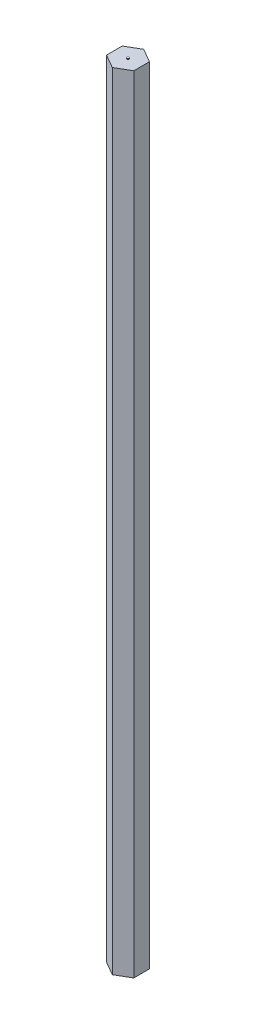
SolidWorks part; units mm, degrees
ref_plane "Front Plane" through (0, 0, 0) normal (0, 0, 1) x (1, 0, 0)
ref_plane "Top Plane" through (0, 0, 0) normal (0, 1, 0) x (1, 0, 0)
ref_plane "Right Plane" through (0, 0, 0) normal (1, 0, 0) x (0, 0, -1)
sketch "Sketch1" plane through (0, 0, 0) normal (0, 1, 0) x (1, 0, 0)
  line L1 (1732.0508, 1000) -> (0, 2000)
  line L2 (0, 2000) -> (-1732.0508, 1000)
  line L3 (-1732.0508, 1000) -> (-1732.0508, -1000)
  line L4 (-1732.0508, -1000) -> (0, -2000)
  line L5 (0, -2000) -> (1732.0508, -1000)
  line L6 (1732.0508, -1000) -> (1732.0508, 1000)
  circle A0 centre (0, 0) radius 2000
  circle A1 centre (0, 0) radius 1732.0508 construction
extrude "Boss-Extrude1" add sketch "Sketch1" along normal blind 100000 contours L5 L6 L1 L2 L3 L4
sketch "Sketch2" plane through (0, 100000, 0) normal (0, 1, 0) x (1, 0, 0)
  circle A0 centre (0, 0) radius 150
  dimension "D1" = 300
extrude "Boss-Extrude2" add sketch "Sketch2" along normal blind 100
